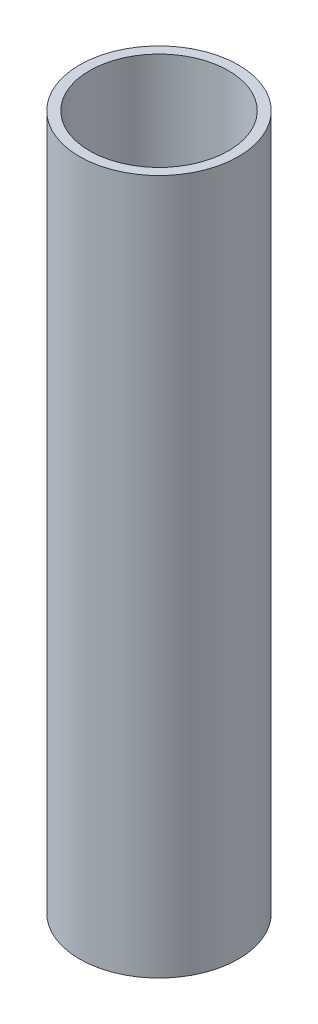
SolidWorks part; units mm, degrees
ref_plane "Alzado" through (0, 0, 0) normal (0, 0, 1) x (1, 0, 0)
ref_plane "Planta" through (0, 0, 0) normal (0, 1, 0) x (1, 0, 0)
ref_plane "Vista lateral" through (0, 0, 0) normal (1, 0, 0) x (0, 0, -1)
sketch "Croquis1" plane through (0, 0, 0) normal (0, 1, 0) x (1, 0, 0)
  circle A0 centre (0, 0) radius 4
  circle A1 centre (0, 0) radius 3.5
  dimension "D1" = 8
  dimension "D2" = 7
extrude "Saliente-Extruir1" add sketch "Croquis1" along normal blind 35
